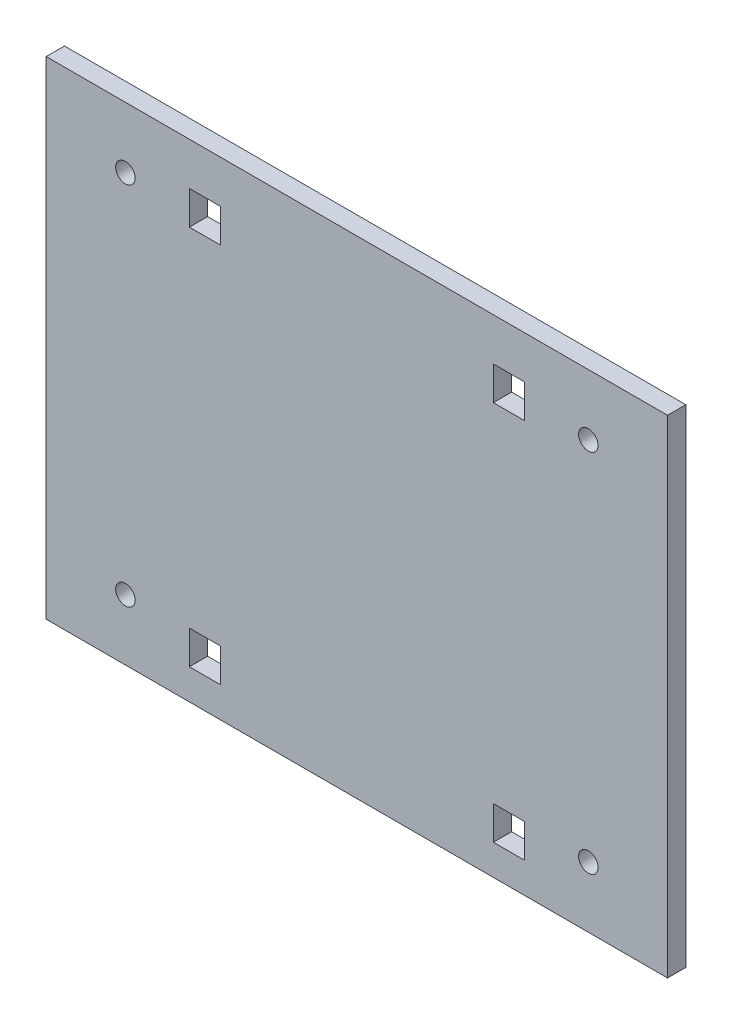
SolidWorks part; units mm, degrees
ref_plane "前视基准面" through (0, 0, 0) normal (0, 0, 1) x (1, 0, 0)
ref_plane "上视基准面" through (0, 0, 0) normal (0, 1, 0) x (1, 0, 0)
ref_plane "右视基准面" through (0, 0, 0) normal (1, 0, 0) x (0, 0, -1)
sketch "草图1" plane through (0, 0, 0) normal (0, 0, 1) x (1, 0, 0)
  line L1 (51, -25.25) -> (-51, -25.25)
  line L2 (51, -25.25) -> (51, -105.25)
  line L3 (51, -105.25) -> (-51, -105.25)
  line L4 (-51, -25.25) -> (-51, -105.25)
  circle A0 centre (-38, -35.25) radius 1.6
  circle A1 centre (-38, -95.25) radius 1.6
  circle A2 centre (38, -95.25) radius 1.6
  circle A3 centre (38, -35.25) radius 1.6
extrude "凸台-拉伸1" add sketch "草图1" along normal blind 3
sketch "草图4" plane through (0, 0, 3) normal (0, 0, 1) x (1, 0, 0)
  line L9 (-27.5, -94.75) -> (-22.4, -94.75)
  line L10 (-27.5, -94.75) -> (-27.5, -100.25)
  line L11 (-27.5, -100.25) -> (-22.4, -100.25)
  line L12 (-22.4, -94.75) -> (-22.4, -100.25)
  line L18 (-51, -105.25) -> (51, -105.25) construction
  line L19 (-51, -25.25) -> (-51, -105.25) construction
  dimension "D1" = 5.1
  dimension "D2" = 5.5
  dimension "D3" = 5
  dimension "D4" = 23.5
extrude "切除-拉伸2" cut sketch "草图4" against normal blind 5
ref_plane "基准面1" through (0, 0, 0) normal (-1, 0, 0) x (0, 0, 1)
mirror "镜向1" about plane through (0, 0, 0) normal (-1, 0, 0) of "切除-拉伸2"
pattern_linear "阵列(线性)1" count 2 spacing 62.5 along (0, 1, 0) of "切除-拉伸2", "镜向1"
